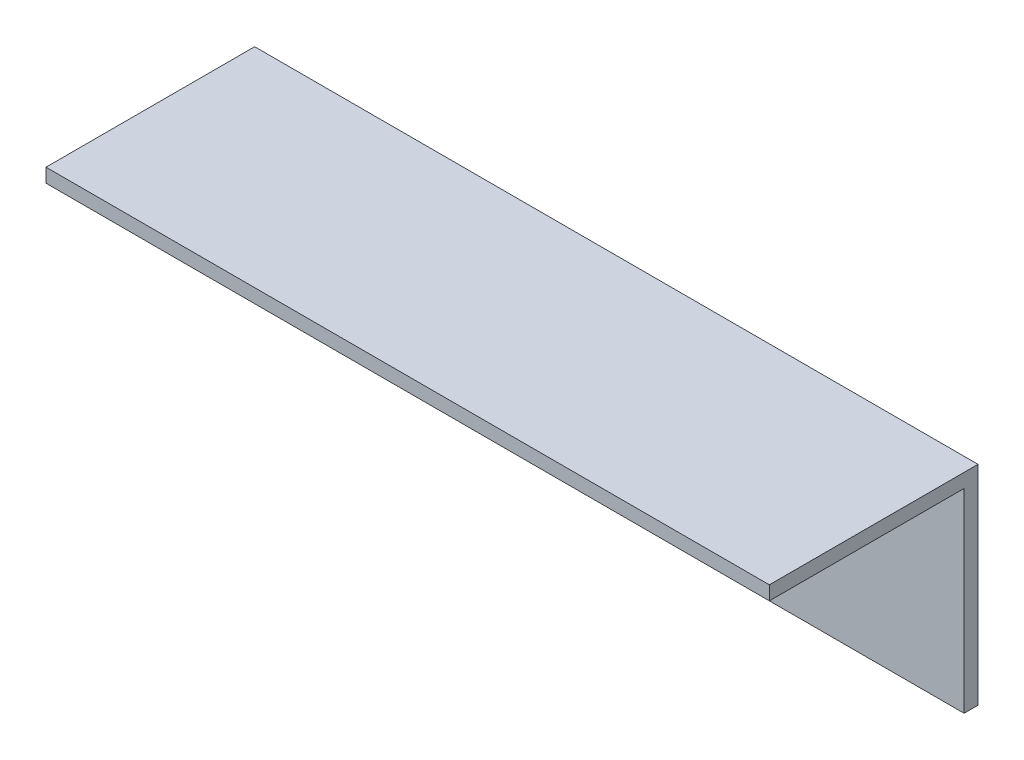
SolidWorks part; units mm, degrees
ref_plane "前基準面" through (0, 0, 0) normal (0, 0, 1) x (1, 0, 0)
ref_plane "上基準面" through (0, 0, 0) normal (0, 1, 0) x (1, 0, 0)
ref_plane "右基準面" through (0, 0, 0) normal (1, 0, 0) x (0, 0, -1)
sketch "草圖1" plane through (0, 0, 0) normal (0, 0, 1) x (1, 0, 0)
  line L1 (0, 0) -> (-104, 0)
  line L2 (0, 0) -> (0, 30)
  line L3 (0, 30) -> (-104, 30)
  line L4 (-104, 0) -> (-104, 30)
  dimension "D1" = 104
  dimension "D2" = 30
extrude "填料-伸長1" add sketch "草圖1" along normal blind 30
sketch "草圖2" plane through (0, 0, 30) normal (0, 0, 1) x (1, 0, 0)
  line L0 (-104, 0) -> (0, 0) construction
  line L1 (-104, 28) -> (0, 28)
  line L2 (-104, 28) -> (-104, 0)
  line L3 (-104, 0) -> (0, 0)
  line L4 (0, 28) -> (0, 0)
  line L5 (-104, 30) -> (-104, 0) construction
  dimension "D1" = 28
  dimension "D2" = 0
  dimension "D3" = 104
  dimension "D4" = 0
extrude "除料-伸長1" cut sketch "草圖2" against normal blind 28
